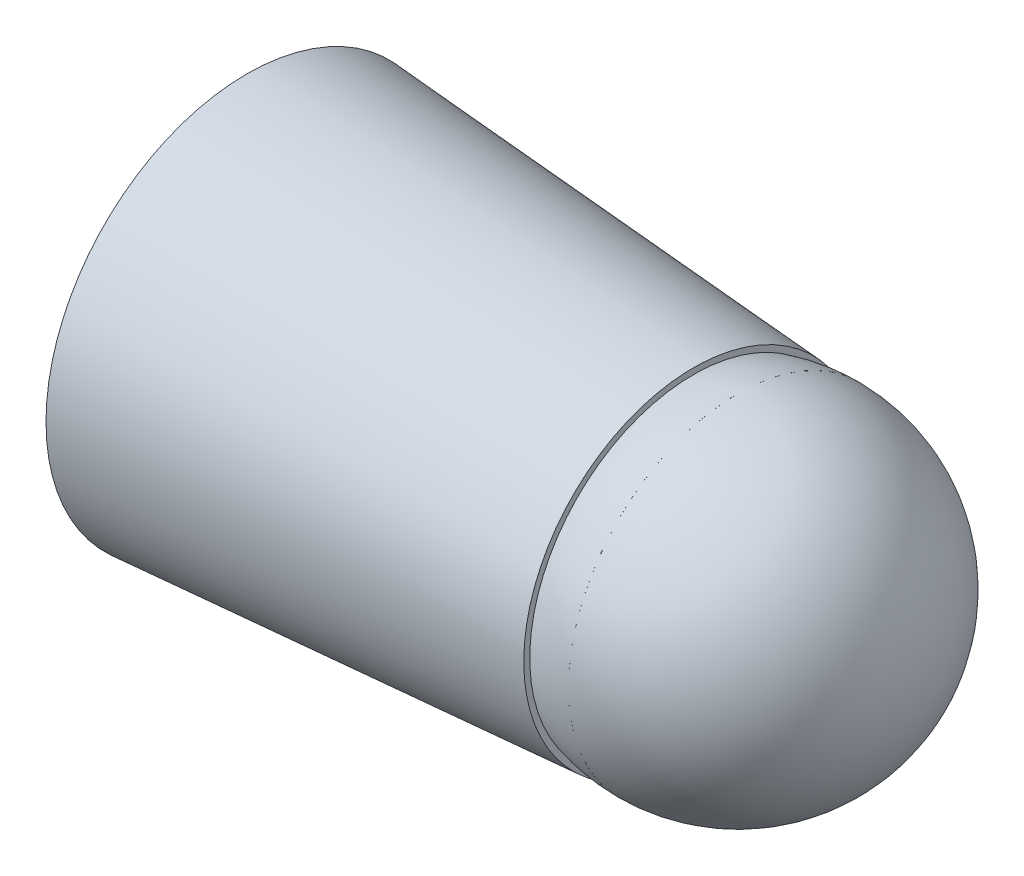
SolidWorks part; units mm, degrees
material "1060 Alloy"
ref_plane "Front Plane" through (0, 0, 0) normal (0, 0, 1) x (1, 0, 0)
ref_plane "Top Plane" through (0, 0, 0) normal (0, 1, 0) x (1, 0, 0)
ref_plane "Right Plane" through (0, 0, 0) normal (1, 0, 0) x (0, 0, -1)
sketch "Sketch1" plane through (0, 0, 0) normal (1, 0, 0) x (0, 0, -1)
  circle A0 centre (0, 0) radius 4.5
  dimension "D1" = 9
extrude "Boss-Extrude1" add sketch "Sketch1" along normal blind 10 draft 4
surface "Surface-Offset1" parameters "D1"=1
sketch "Sketch2" plane through (11, 0, 0) normal (1, 0, 0) x (0, 0, -1)
  line L0 (0, 3.8007) -> (0, -3.8007) construction
  line L1 (0, 3.8007) -> (0, -3.8007)
  arc A0 (0, -3.8007) -> (0, 3.8007) centre (0, 0) ccw
  circle A1 centre (0, 0) radius 3.8007 construction
  dimension "D1" = 3.8007
revolve "Revolve1" add sketch "Sketch2" angle 360 about L0
